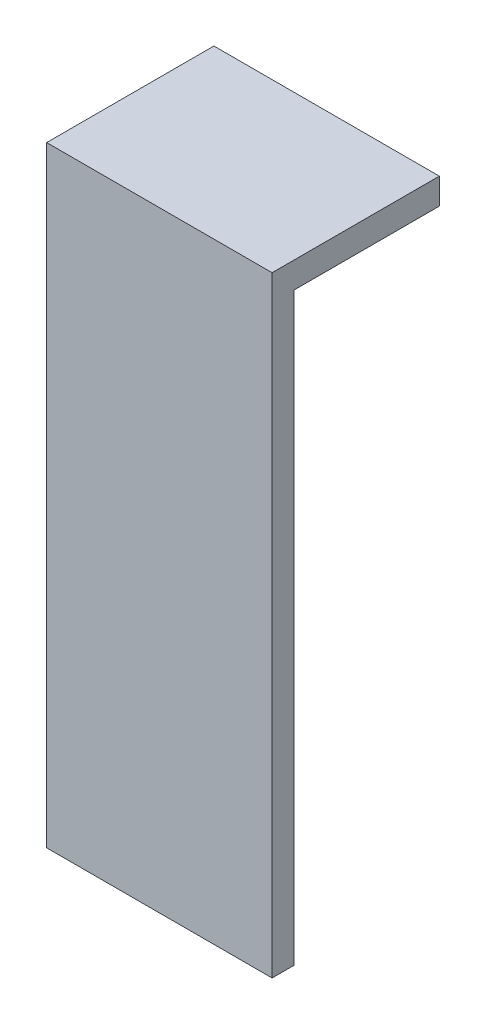
SolidWorks part; units mm, degrees
ref_plane "Front Plane" through (0, 0, 0) normal (0, 0, 1) x (1, 0, 0)
ref_plane "Top Plane" through (0, 0, 0) normal (0, 1, 0) x (1, 0, 0)
ref_plane "Right Plane" through (0, 0, 0) normal (1, 0, 0) x (0, 0, -1)
sketch "Sketch1" plane through (0, 0, 0) normal (0, 1, 0) x (1, 0, 0)
  line L1 (-4.2545, 0.762) -> (3.6195, 0.762)
  line L2 (-4.2545, 0.762) -> (-4.2545, 0)
  line L3 (-4.2545, 0) -> (3.6195, 0)
  line L4 (3.6195, 0.762) -> (3.6195, 0)
  point P4 (3.6195, 0.381)
  dimension "D1" = 7.874
  dimension "D2" = 0.762
extrude "Boss-Extrude1" add sketch "Sketch1" along normal blind 21.336
sketch "Sketch2" plane through (0, 0, -0.762) normal (0, 0, -1) x (-1, 0, 0)
  line L0 (-3.6195, 21.336) -> (-3.6195, 0) construction
  line L1 (-3.6195, 21.336) -> (4.2545, 21.336)
  line L2 (-3.6195, 21.336) -> (-3.6195, 20.4278)
  line L3 (-3.6195, 20.4278) -> (4.2545, 20.4278)
  line L4 (4.2545, 21.336) -> (4.2545, 20.4278)
  line L5 (4.2545, 21.336) -> (4.2545, 0) construction
extrude "Boss-Extrude2" add sketch "Sketch2" along normal blind 5.08
